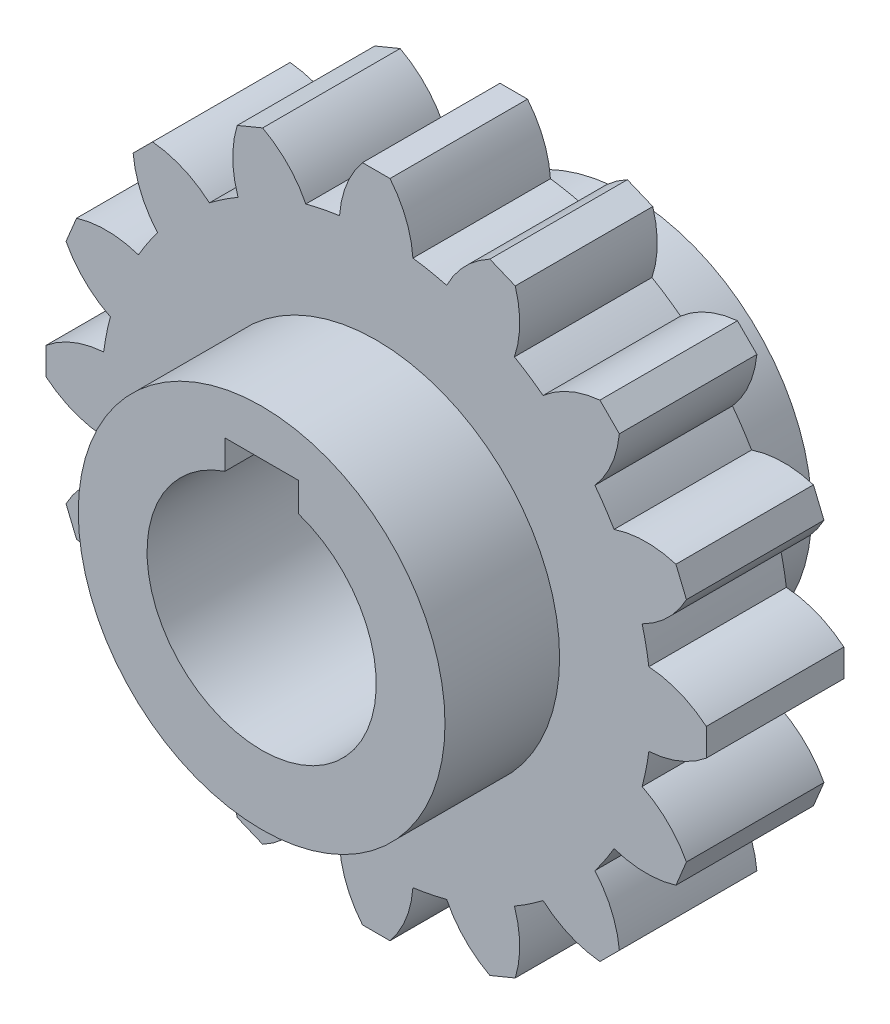
SolidWorks part; units mm, degrees
ref_plane "Front Plane" through (0, 0, 0) normal (0, 0, 1) x (1, 0, 0)
ref_plane "Top Plane" through (0, 0, 0) normal (0, 1, 0) x (1, 0, 0)
ref_plane "Right Plane" through (0, 0, 0) normal (1, 0, 0) x (0, 0, -1)
sketch "Sketch1" plane through (0, 0, 0) normal (0, 0, 1) x (1, 0, 0)
  line L1 (-1.5, 36) -> (1.5, 36)
  line L2 (12.3908, 33.8337) -> (15.1624, 32.6856)
  line L3 (24.3952, 26.5165) -> (26.5165, 24.3952)
  line L4 (32.6856, 15.1624) -> (33.8337, 12.3908)
  line L5 (36, 1.5) -> (36, -1.5)
  line L6 (33.8337, -12.3908) -> (32.6856, -15.1624)
  line L7 (26.5165, -24.3952) -> (24.3952, -26.5165)
  line L8 (15.1624, -32.6856) -> (12.3908, -33.8337)
  line L9 (1.5, -36) -> (-1.5, -36)
  line L10 (-12.3908, -33.8337) -> (-15.1624, -32.6856)
  line L11 (-24.3952, -26.5165) -> (-26.5165, -24.3952)
  line L12 (-32.6856, -15.1624) -> (-33.8337, -12.3908)
  line L13 (-36, -1.5) -> (-36, 1.5)
  line L14 (-33.8337, 12.3908) -> (-32.6856, 15.1624)
  line L15 (-26.5165, 24.3952) -> (-24.3952, 26.5165)
  line L16 (-15.1624, 32.6856) -> (-12.3908, 33.8337)
  arc A0 (-4, 29.7321) -> (-7.6825, 28.9996) centre (0, 0) ccw
  arc A1 (1.5, 36) -> (4, 29.7321) centre (-6.9748, 28.9873) cw
  arc A2 (-1.5, 36) -> (-4, 29.7321) centre (6.9748, 28.9873) ccw
  arc A3 (12.3908, 33.8337) -> (7.6825, 28.9996) centre (17.5368, 24.1116) ccw
  arc A4 (15.1624, 32.6856) -> (15.0735, 25.9382) centre (4.6491, 29.4499) cw
  arc A5 (24.3952, 26.5165) -> (18.1954, 23.8522) centre (25.429, 15.5652) ccw
  arc A6 (26.5165, 24.3952) -> (23.8522, 18.1954) centre (15.5652, 25.429) cw
  arc A7 (32.6856, 15.1624) -> (25.9382, 15.0735) centre (29.4499, 4.6491) ccw
  arc A8 (33.8337, 12.3908) -> (28.9996, 7.6825) centre (24.1116, 17.5368) cw
  arc A9 (36, 1.5) -> (29.7321, 4) centre (28.9873, -6.9748) ccw
  arc A10 (36, -1.5) -> (29.7321, -4) centre (28.9873, 6.9748) cw
  arc A11 (33.8337, -12.3908) -> (28.9996, -7.6825) centre (24.1116, -17.5368) ccw
  arc A12 (32.6856, -15.1624) -> (25.9382, -15.0735) centre (29.4499, -4.6491) cw
  arc A13 (26.5165, -24.3952) -> (23.8522, -18.1954) centre (15.5652, -25.429) ccw
  arc A14 (24.3952, -26.5165) -> (18.1954, -23.8522) centre (25.429, -15.5652) cw
  arc A15 (15.1624, -32.6856) -> (15.0735, -25.9382) centre (4.6491, -29.4499) ccw
  arc A16 (12.3908, -33.8337) -> (7.6825, -28.9996) centre (17.5368, -24.1116) cw
  arc A17 (1.5, -36) -> (4, -29.7321) centre (-6.9748, -28.9873) ccw
  arc A18 (-1.5, -36) -> (-4, -29.7321) centre (6.9748, -28.9873) cw
  arc A19 (-12.3908, -33.8337) -> (-7.6825, -28.9996) centre (-17.5368, -24.1116) ccw
  arc A20 (-15.1624, -32.6856) -> (-15.0735, -25.9382) centre (-4.6491, -29.4499) cw
  arc A21 (-24.3952, -26.5165) -> (-18.1954, -23.8522) centre (-25.429, -15.5652) ccw
  arc A22 (-26.5165, -24.3952) -> (-23.8522, -18.1954) centre (-15.5652, -25.429) cw
  arc A23 (-32.6856, -15.1624) -> (-25.9382, -15.0735) centre (-29.4499, -4.6491) ccw
  arc A24 (-33.8337, -12.3908) -> (-28.9996, -7.6825) centre (-24.1116, -17.5368) cw
  arc A25 (-36, -1.5) -> (-29.7321, -4) centre (-28.9873, 6.9748) ccw
  arc A26 (-36, 1.5) -> (-29.7321, 4) centre (-28.9873, -6.9748) cw
  arc A27 (-33.8337, 12.3908) -> (-28.9996, 7.6825) centre (-24.1116, 17.5368) ccw
  arc A28 (-32.6856, 15.1624) -> (-25.9382, 15.0735) centre (-29.4499, 4.6491) cw
  arc A29 (-26.5165, 24.3952) -> (-23.8522, 18.1954) centre (-15.5652, 25.429) ccw
  arc A30 (-24.3952, 26.5165) -> (-18.1954, 23.8522) centre (-25.429, 15.5652) cw
  arc A31 (-15.1624, 32.6856) -> (-15.0735, 25.9382) centre (-4.6491, 29.4499) ccw
  arc A32 (-12.3908, 33.8337) -> (-7.6825, 28.9996) centre (-17.5368, 24.1116) cw
  arc A33 (7.6825, 28.9996) -> (4, 29.7321) centre (0, 0) ccw
  arc A34 (18.1954, 23.8522) -> (15.0735, 25.9382) centre (0, 0) ccw
  arc A35 (25.9382, 15.0735) -> (23.8522, 18.1954) centre (0, 0) ccw
  arc A36 (29.7321, 4) -> (28.9996, 7.6825) centre (0, 0) ccw
  arc A37 (28.9996, -7.6825) -> (29.7321, -4) centre (0, 0) ccw
  arc A38 (23.8522, -18.1954) -> (25.9382, -15.0735) centre (0, 0) ccw
  arc A39 (15.0735, -25.9382) -> (18.1954, -23.8522) centre (0, 0) ccw
  arc A40 (4, -29.7321) -> (7.6825, -28.9996) centre (0, 0) ccw
  arc A41 (-7.6825, -28.9996) -> (-4, -29.7321) centre (0, 0) ccw
  arc A42 (-18.1954, -23.8522) -> (-15.0735, -25.9382) centre (0, 0) ccw
  arc A43 (-25.9382, -15.0735) -> (-23.8522, -18.1954) centre (0, 0) ccw
  arc A44 (-29.7321, -4) -> (-28.9996, -7.6825) centre (0, 0) ccw
  arc A45 (-28.9996, 7.6825) -> (-29.7321, 4) centre (0, 0) ccw
  arc A46 (-23.8522, 18.1954) -> (-25.9382, 15.0735) centre (0, 0) ccw
  arc A47 (-15.0735, 25.9382) -> (-18.1954, 23.8522) centre (0, 0) ccw
  point P8 (0, 36)
  point P105 (0, 0)
  dimension "D1" = 60
  dimension "D4" = 11
  dimension "D3" = 3
  dimension "D5" = 8
  dimension "D6" = 16
extrude "Boss-Extrude1" add sketch "Sketch1" along normal mid plane 15
sketch "Sketch2" plane through (0, 0, 0) normal (0, 0, 1) x (1, 0, 0)
  circle A0 centre (0, 0) radius 20
  dimension "D1" = 40
extrude "Boss-Extrude2" add sketch "Sketch2" along normal mid plane 40
sketch "Sketch3" plane through (0, 0, 20) normal (0, 0, 1) x (1, 0, 0)
  line L1 (-4, 11.8427) -> (-4, 15)
  line L2 (-4, 15) -> (4, 15)
  line L3 (4, 15) -> (4, 11.8427)
  arc A0 (-4, 11.8427) -> (4, 11.8427) centre (0, 0) ccw
  dimension "D1" = 25
  dimension "D3" = 8
extrude "Cut-Extrude1" cut sketch "Sketch3" against normal through all
